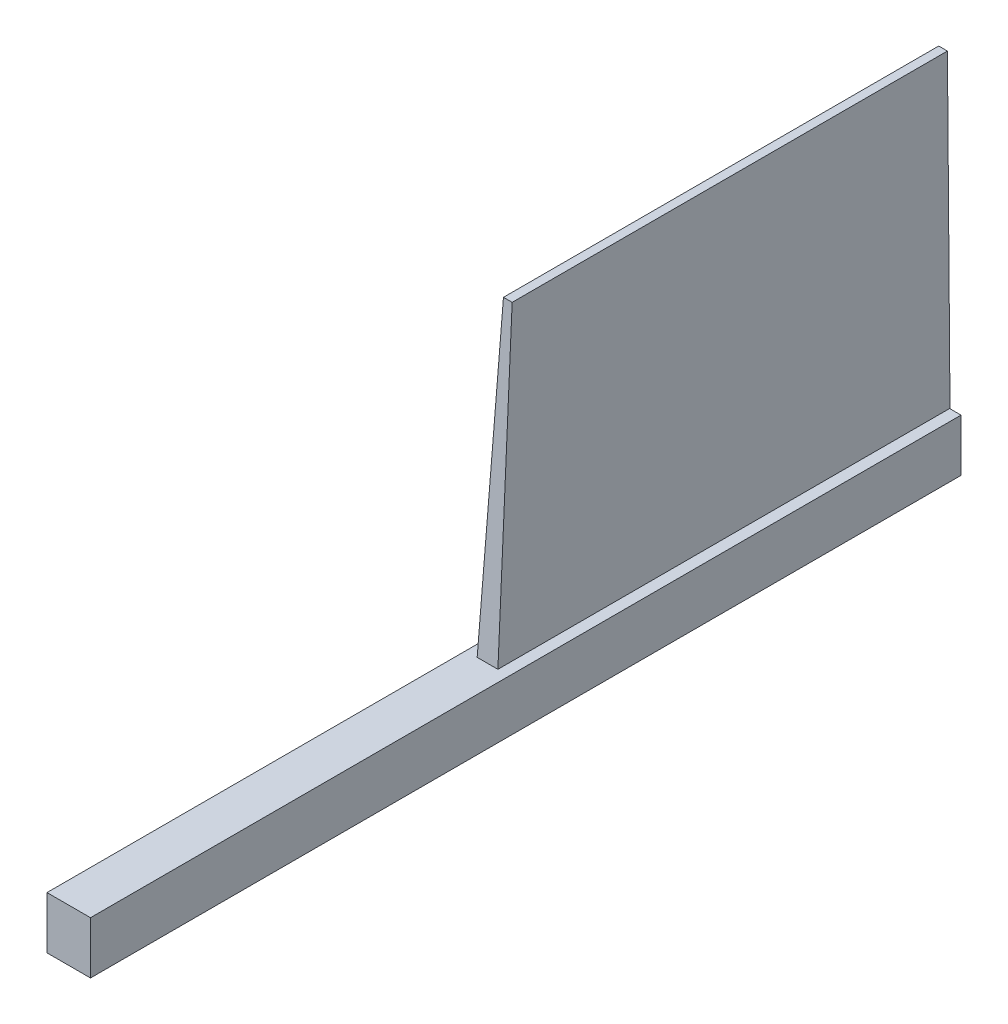
SolidWorks part; units mm, degrees
material "ABS"
ref_plane "Plan de face" through (0, 0, 0) normal (0, 0, 1) x (1, 0, 0)
ref_plane "Plan de dessus" through (0, 0, 0) normal (0, 1, 0) x (1, 0, 0)
ref_plane "Plan de droite" through (0, 0, 0) normal (1, 0, 0) x (0, 0, -1)
sketch "Esquisse1" plane through (0, 0, 0) normal (0, 0, 1) x (1, 0, 0)
  line L1 (-5, 6) -> (5, 6)
  line L2 (-5, 6) -> (-5, -6)
  line L3 (-5, -6) -> (5, -6)
  line L4 (5, 6) -> (5, -6)
  line L5 (-5, 6) -> (5, -6) construction
  line L6 (-5, -6) -> (5, 6) construction
  point P0 (0, 0)
  dimension "D1" = 12
  dimension "D2" = 10
extrude "Boss.-Extru.1" add sketch "Esquisse1" along normal blind 200
ref_plane "Plan1" through (0, 76, 0) normal (0, 1, 0) x (1, 0, 0)
sketch "Esquisse3" plane through (0, 76, 0) normal (0, 1, 0) x (1, 0, 0)
  line L1 (-1, 0.8761) -> (1, 0.8761)
  line L2 (-1, 0.8761) -> (-1, -99.1239)
  line L3 (-1, -99.1239) -> (1, -99.1239)
  line L4 (1, 0.8761) -> (1, -99.1239)
  point P5 (0, 0.8761)
  dimension "D1" = 100
  dimension "D2" = 2
sketch "Esquisse4" plane through (0, 0, 0) normal (0, 1, 0) x (1, 0, 0)
  line L1 (-2.5, 0.02) -> (2.5, 0.02)
  line L2 (-2.5, 0.02) -> (-2.5, -104.1833)
  line L3 (-2.5, -104.1833) -> (2.5, -104.1833)
  line L4 (2.5, 0.02) -> (2.5, -104.1833)
  line L7 (-5, -200) -> (-5, 0) construction
  dimension "D1" = 5
  dimension "D2" = 2.5
loft "Lissage2" add profiles "Esquisse4", "Esquisse3"
